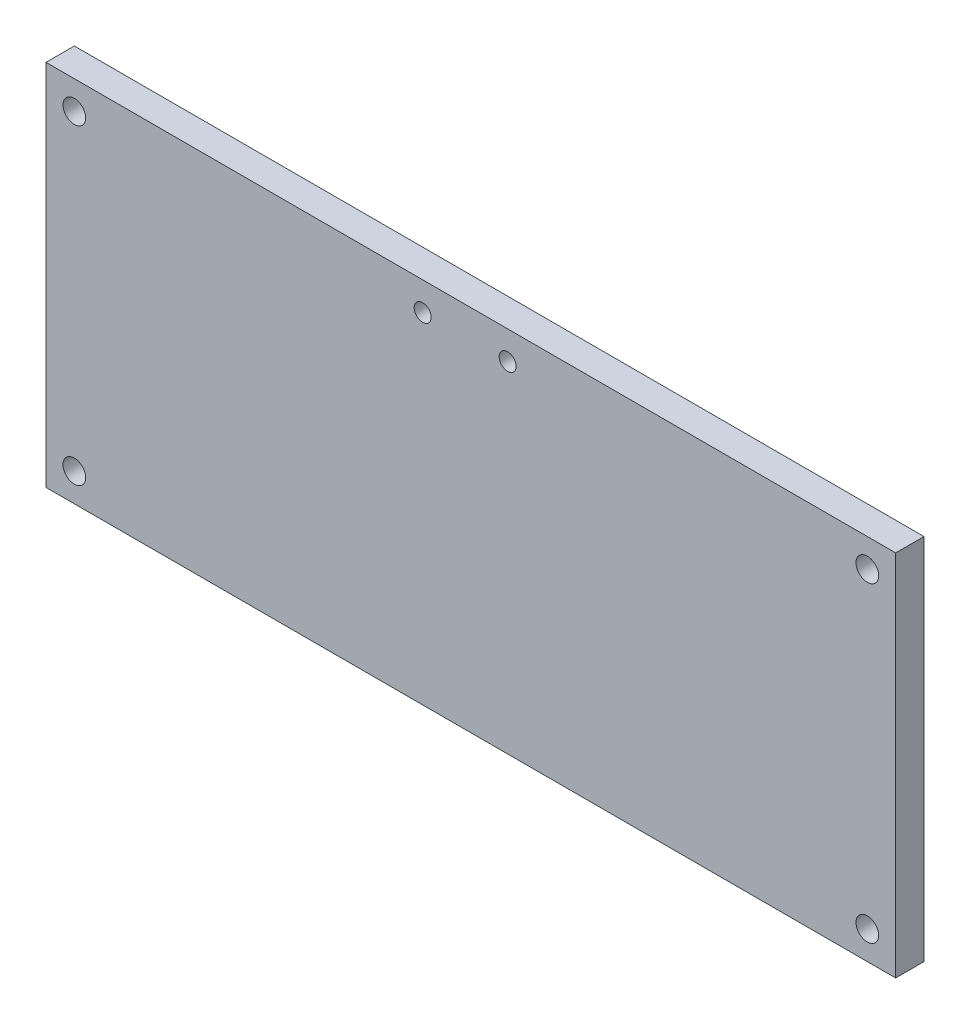
SolidWorks part; units mm, degrees
ref_plane "Plan de face" through (0, 0, 0) normal (0, 0, 1) x (1, 0, 0)
ref_plane "Plan de dessus" through (0, 0, 0) normal (0, 1, 0) x (1, 0, 0)
ref_plane "Plan de droite" through (0, 0, 0) normal (1, 0, 0) x (0, 0, -1)
sketch "Esquisse1" plane through (0, 0, 0) normal (0, 0, 1) x (1, 0, 0)
  line L0 (-78.3107, 0) -> (221.6893, 0)
  line L1 (221.6893, 0) -> (221.6893, 130)
  line L2 (221.6893, 130) -> (-78.3107, 130)
  line L3 (-78.3107, 130) -> (-78.3107, 0)
  dimension "D1" = 300
  dimension "D2" = 130
extrude "Boss.-Extru.1" add sketch "Esquisse1" along normal blind 10
sketch "Esquisse2" plane through (0, 0, 10) normal (0, 0, 1) x (1, 0, 0)
  line L0 (-78.3107, 130) -> (-78.3107, 0) construction
  line L1 (221.6893, 130) -> (-78.3107, 130) construction
  line L3 (-78.3107, 0) -> (221.6893, 0) construction
  line L4 (221.6893, 0) -> (221.6893, 130) construction
  circle A0 centre (-68.3107, 120) radius 4
  circle A1 centre (-68.3107, 10) radius 4
  circle A2 centre (211.6893, 10) radius 4
  circle A3 centre (211.6893, 120) radius 4
  dimension "D1" = 10
  dimension "D3" = 10
  dimension "D6" = 8
  dimension "D7" = 10
  dimension "D2" = 10
  dimension "D4" = 10
  dimension "D5" = 10
  dimension "D8" = 10
  dimension "D9" = 10
extrude "Enlèv. mat.-Extru.1" cut sketch "Esquisse2" against normal through all
sketch "Esquisse3" plane through (0, 0, 10) normal (0, 0, 1) x (1, 0, 0)
  circle A0 centre (84.6893, 120) radius 3
  circle A1 centre (54.6893, 120) radius 3
extrude "Enlèv. mat.-Extru.2" cut sketch "Esquisse3" against normal through all
